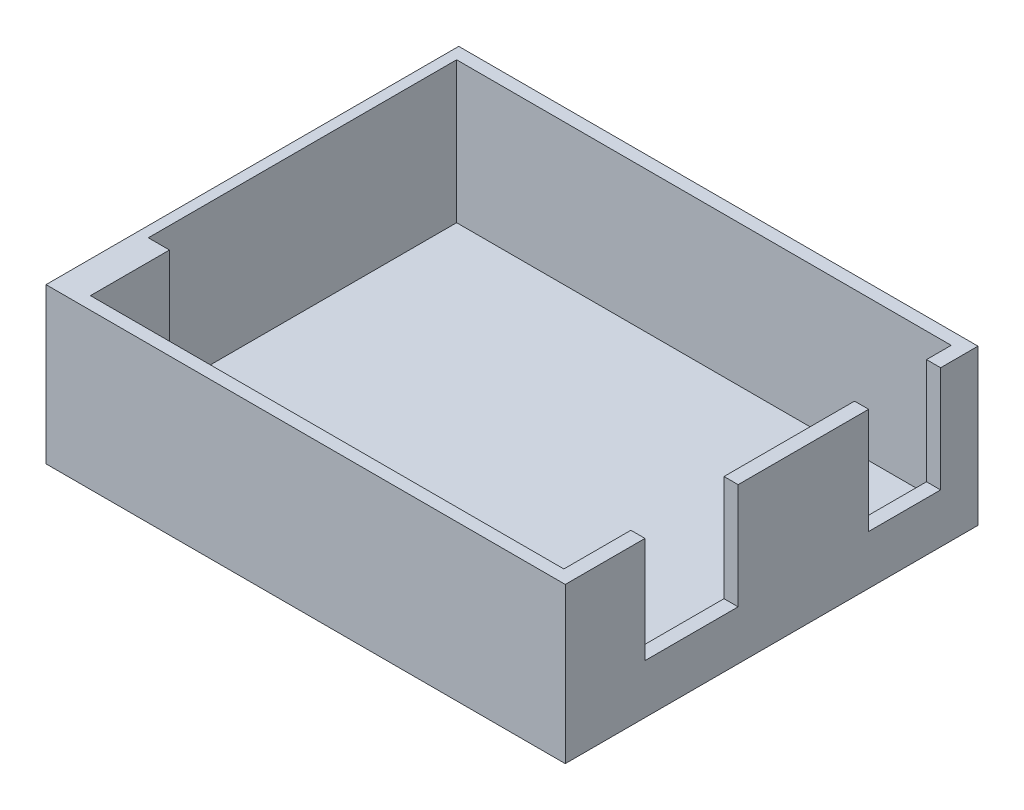
SolidWorks part; units mm, degrees
ref_plane "Спереди" through (0, 0, 0) normal (0, 0, 1) x (1, 0, 0)
ref_plane "Сверху" through (0, 0, 0) normal (0, 1, 0) x (1, 0, 0)
ref_plane "Справа" through (0, 0, 0) normal (1, 0, 0) x (0, 0, -1)
sketch "Эскиз1" plane through (0, 0, 0) normal (0, 1, 0) x (1, 0, 0)
  line L1 (0, 0) -> (73.6, 0)
  line L2 (0, 0) -> (0, -58.5)
  line L3 (0, -58.5) -> (73.6, -58.5)
  line L4 (73.6, 0) -> (73.6, -58.5)
  dimension "D1" = 73.6
  dimension "D2" = 58.5
extrude "Бобышка-Вытянуть1" add sketch "Эскиз1" along normal blind 22
sketch "Эскиз3" plane through (0, 22, 0) normal (0, 1, 0) x (1, 0, 0)
  line L0 (73.6, 0) -> (0, 0) construction
  line L1 (1.5, -1.8) -> (71.6, -1.8)
  line L2 (1.5, -1.8) -> (1.5, -45.5)
  line L3 (1.5, -45.5) -> (4.5, -45.5)
  line L4 (71.6, -15.5) -> (71.6, -34)
  line L6 (0, 0) -> (0, -58.5) construction
  line L7 (0, -58.5) -> (73.6, -58.5) construction
  line L8 (71.6, -1.8) -> (71.6, -5.3)
  line L9 (71.6, -56.7) -> (71.6, -47.2)
  line L10 (4.5, -45.5) -> (4.5, -56.7)
  line L11 (4.5, -56.7) -> (71.6, -56.7)
  line L13 (71.6, -5.3) -> (73.6, -5.3)
  line L15 (71.6, -15.5) -> (73.6, -15.5)
  line L16 (73.6, -5.3) -> (73.6, -15.5)
  line L17 (71.6, -34) -> (73.6, -34)
  line L19 (71.6, -47.2) -> (73.6, -47.2)
  line L20 (73.6, -34) -> (73.6, -47.2)
  point P23 (71.6, -6)
  point P24 (71.6, -16)
  point P25 (71.6, -34)
  point P26 (71.6, -47)
  point P27 (71.6, -6)
  point P29 (4.5, -45)
  point P30 (71.6, -16)
  point P31 (71.6, -34)
  point P32 (71.6, -47)
  dimension "D1" = 1.8
  dimension "D3" = 1.5
  dimension "D4" = 13
  dimension "D5" = 1.8
  dimension "D6" = 4.5
  dimension "D7" = 3.5
  dimension "D8" = 10.2
  dimension "D9" = 18.5
  dimension "D10" = 13.2
  dimension "D11" = 9.5
extrude "Вырез-Вытянуть2" cut sketch "Эскиз3" against normal blind 20
sketch "Эскиз4" plane through (0, 2, 0) normal (0, 1, 0) x (1, 0, 0)
  line L1 (71.6, -5.3) -> (73.6, -5.3)
  line L2 (71.6, -5.3) -> (71.6, -15.5)
  line L3 (71.6, -15.5) -> (73.6, -15.5)
  line L4 (73.6, -5.3) -> (73.6, -15.5)
  line L5 (71.6, -34) -> (73.6, -34)
  line L6 (71.6, -34) -> (71.6, -47.2)
  line L7 (71.6, -47.2) -> (73.6, -47.2)
  line L8 (73.6, -34) -> (73.6, -47.2)
extrude "Бобышка-Вытянуть2" add sketch "Эскиз4" along normal blind 5
